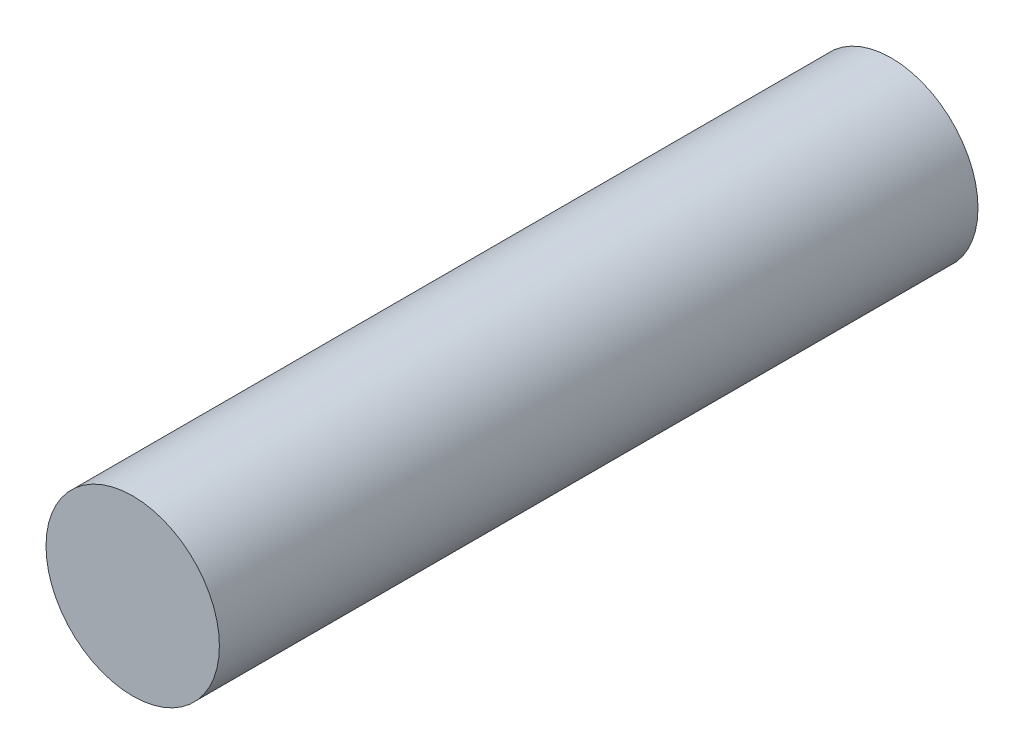
SolidWorks part; units mm, degrees
ref_plane "Front Plane" through (0, 0, 0) normal (0, 0, 1) x (1, 0, 0)
ref_plane "Top Plane" through (0, 0, 0) normal (0, 1, 0) x (1, 0, 0)
ref_plane "Right Plane" through (0, 0, 0) normal (1, 0, 0) x (0, 0, -1)
sketch "Sketch1" plane through (0, 0, 0) normal (0, 0, 1) x (1, 0, 0)
  circle A0 centre (-2.9676, 0.4213) radius 4
  dimension "D1" = 8
extrude "Boss-Extrude1" add sketch "Sketch1" along normal blind 35
